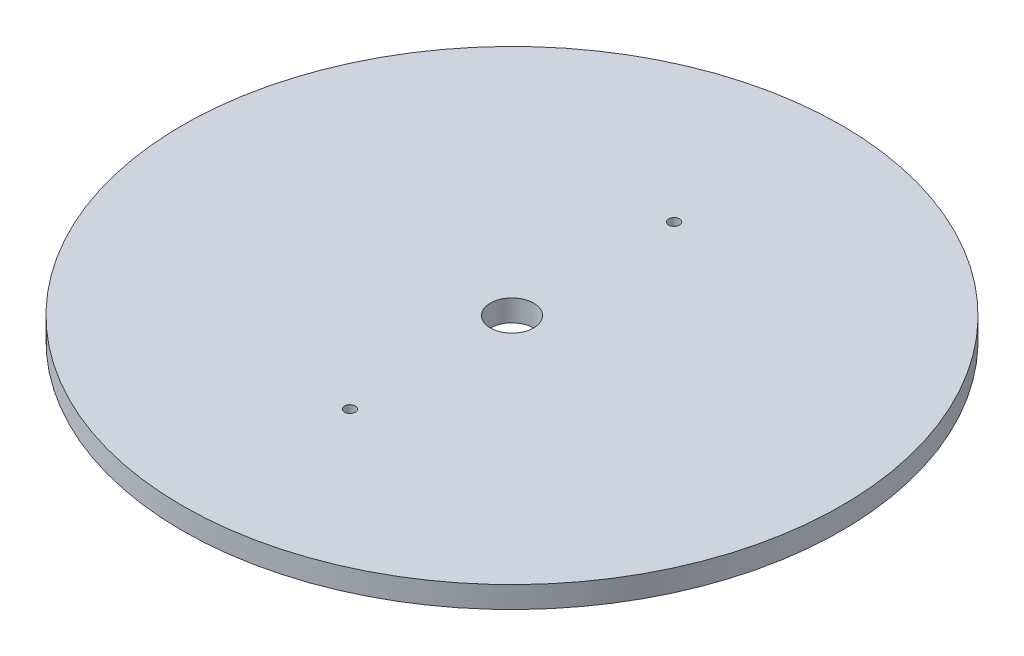
SolidWorks part; units mm, degrees
material "1345 Alloy"
ref_plane "Front Plane" through (0, 0, 0) normal (0, 0, 1) x (1, 0, 0)
ref_plane "Top Plane" through (0, 0, 0) normal (0, 1, 0) x (1, 0, 0)
ref_plane "Right Plane" through (0, 0, 0) normal (1, 0, 0) x (0, 0, -1)
sketch "Sketch1" plane through (0, 0, 0) normal (0, 1, 0) x (1, 0, 0)
  circle A0 centre (0, 0) radius 30.5
extrude "Boss-Extrude1" add sketch "Sketch1" along normal blind 2
sketch "Sketch2" plane through (0, 2, 0) normal (0, 1, 0) x (1, 0, 0)
  circle A0 centre (0, 0) radius 2
extrude "Cut-Extrude1" cut sketch "Sketch2" against normal through all
sketch "Sketch4" plane through (0, 2, 0) normal (0, 1, 0) x (1, 0, 0)
  line L0 (0, 26) -> (0, 19.1972) construction
  line L1 (-246.4035, 0) -> (246.4035, 0) construction
  line L2 (0, 0) -> (42.4175, 0) construction
  circle A0 centre (0, 15) radius 0.5
  circle A1 centre (0, -15) radius 0.5
  dimension "D1" = 15
extrude "Cut-Extrude2" cut sketch "Sketch4" against normal through all
sketch "Sketch5" plane through (0, 0, 0) normal (0, -1, 0) x (1, 0, 0)
  line L0 (0, 26) -> (0, 15) construction
  line L1 (0.6, 26) -> (0.6, 15)
  line L2 (-0.6, 26) -> (-0.6, 15)
  line L3 (0, 0) -> (61.6245, 0) construction
  line L5 (0, -26) -> (0, -15) construction
  line L6 (0.6, -26) -> (0.6, -15)
  line L7 (-0.6, -26) -> (-0.6, -15)
  arc A0 (0.6, 26) -> (-0.6, 26) centre (0, 26) ccw
  arc A1 (-0.6, 15) -> (0.6, 15) centre (0, 15) ccw
  arc A2 (0.6, -26) -> (-0.6, -26) centre (0, -26) cw
  arc A3 (-0.6, -15) -> (0.6, -15) centre (0, -15) cw
  point P4 (0, 20.5)
  point P13 (0, -20.5)
extrude "Cut-Extrude3" cut sketch "Sketch5" against normal blind 0.5
